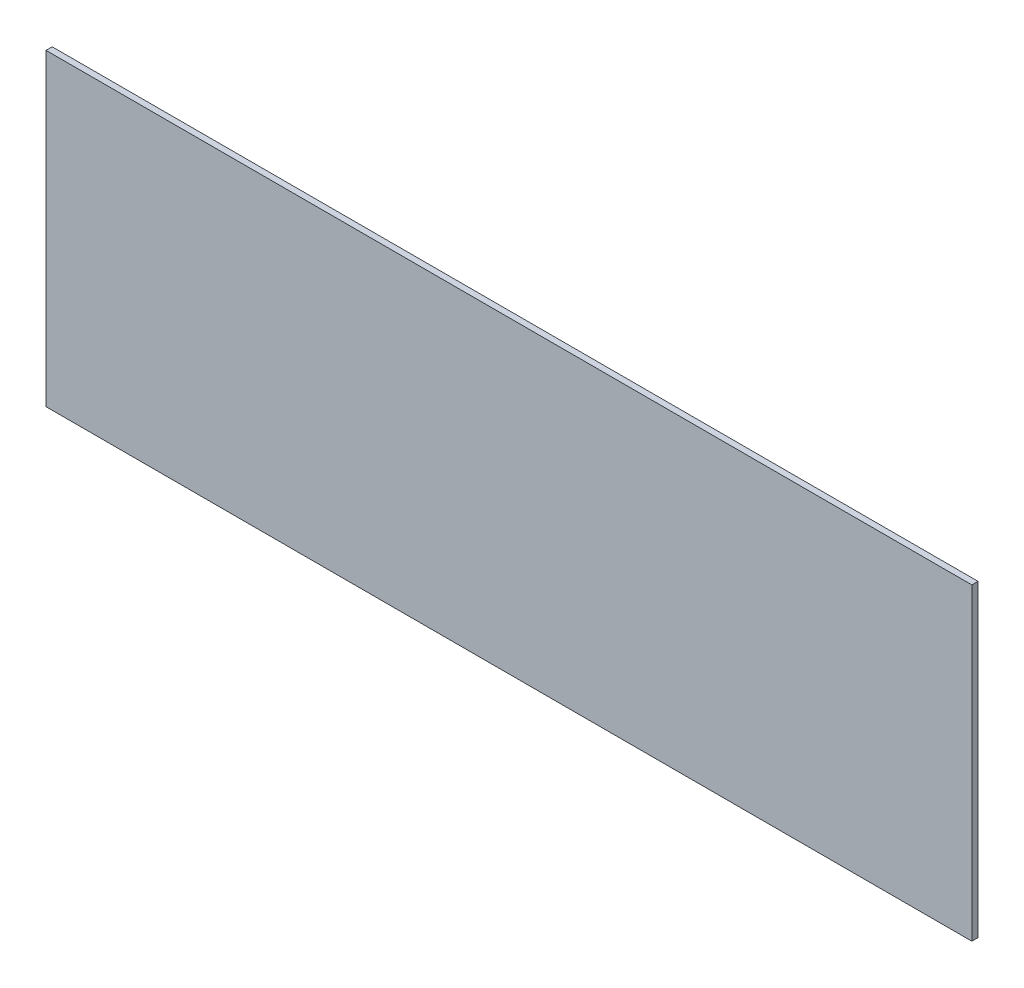
SolidWorks part; units mm, degrees
ref_plane "前视基准面" through (0, 0, 0) normal (0, 0, 1) x (1, 0, 0)
ref_plane "上视基准面" through (0, 0, 0) normal (0, 1, 0) x (1, 0, 0)
ref_plane "右视基准面" through (0, 0, 0) normal (1, 0, 0) x (0, 0, -1)
sketch "草图1" plane through (0, 0, 0) normal (0, 0, 1) x (1, 0, 0)
  line L1 (-37.5, 12.5) -> (37.5, 12.5)
  line L2 (-37.5, 12.5) -> (-37.5, -12.5)
  line L3 (-37.5, -12.5) -> (37.5, -12.5)
  line L4 (37.5, 12.5) -> (37.5, -12.5)
  line L5 (-37.5, 12.5) -> (37.5, -12.5) construction
  line L6 (-37.5, -12.5) -> (37.5, 12.5) construction
  point P0 (0, 0)
  dimension "D1" = 75
  dimension "D2" = 25
extrude "凸台-拉伸1" add sketch "草图1" along normal blind 0.5
